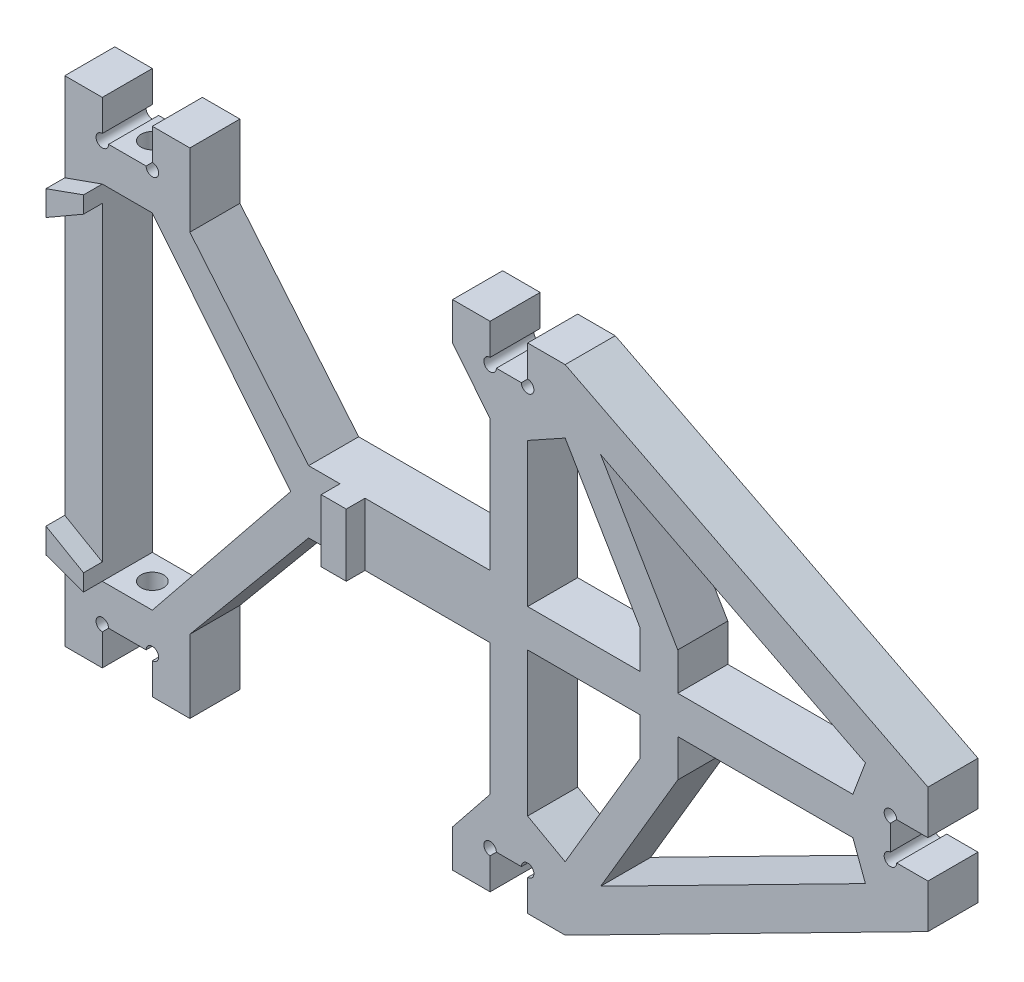
SolidWorks part; units mm, degrees
ref_plane "前视基准面" through (0, 0, 0) normal (0, 0, 1) x (1, 0, 0)
ref_plane "上视基准面" through (0, 0, 0) normal (0, 1, 0) x (1, 0, 0)
ref_plane "右视基准面" through (0, 0, 0) normal (1, 0, 0) x (0, 0, -1)
sketch "草图1" plane through (0, 0, 0) normal (0, 0, 1) x (1, 0, 0)
  line L12 (66, -1) -> (66, 1)
  line L13 (69, -5) -> (40, -19.75)
  line L14 (40, -19.75) -> (37, -19.75)
  line L15 (34.5, -16.75) -> (36.5, -16.75)
  line L16 (31, -16.75) -> (31, -19.75)
  line L17 (34, 13) -> (34, 2.5)
  line L18 (34, 13) -> (31, 16.75)
  line L19 (31, 19.75) -> (34, 19.75)
  line L20 (34, 19.75) -> (34, 17.25)
  line L21 (34.5, 16.75) -> (36.5, 16.75)
  line L22 (37, 13) -> (37, 1.5)
  line L23 (34, -19.75) -> (31, -19.75)
  line L24 (34, -13) -> (31, -16.75)
  line L25 (34, -19.75) -> (34, -17.25)
  line L26 (42.8383, -14.9406) -> (49, -4.5)
  line L27 (46, -1.5) -> (37, -1.5)
  line L28 (34, -2.5) -> (34, -13)
  line L29 (40, 14.6667) -> (46, 4.5)
  line L30 (46, 4.5) -> (46, 1.5)
  line L31 (63, 1.5) -> (64, 4.1774)
  line L32 (49, -1.5) -> (49, -4.5)
  line L33 (49, 4.5) -> (49, 1.5)
  line L34 (49, 1.5) -> (63, 1.5)
  line L35 (37, -17.25) -> (37, -19.75)
  line L36 (37, -1.5) -> (37, -13)
  line L37 (46, -1.5) -> (46, -4.5)
  line L38 (37, 19.75) -> (37, 17.25)
  line L39 (37, -13) -> (40, -14.6667)
  line L40 (46, -4.5) -> (40, -14.6667)
  line L41 (37, 13) -> (40, 14.6667)
  line L42 (37, 1.5) -> (46, 1.5)
  line L43 (42.8383, 14.9406) -> (64, 4.1774)
  line L44 (42.8383, -14.9406) -> (64, -4.1774)
  line L45 (49, 4.5) -> (42.8383, 14.9406)
  line L46 (66.5, 1.5) -> (69, 1.5)
  line L47 (69, 5) -> (69, 1.5)
  line L48 (63, -1.5) -> (49, -1.5)
  line L49 (37, 19.75) -> (40, 19.75)
  line L50 (40, 19.75) -> (69, 5)
  line L51 (31, 19.75) -> (31, 16.75)
  line L52 (69, -5) -> (69, -1.5)
  line L53 (66.5, -1.5) -> (69, -1.5)
  line L54 (63, -1.5) -> (64, -4.1774)
  line L55 (34, -2.5) -> (19.4926, -2.5)
  line L56 (34, 2.5) -> (19.4926, 2.5)
  line L57 (10, -13.9159) -> (19.4926, -2.5)
  line L58 (10, -19.75) -> (10, -13.9159)
  line L59 (10, -19.75) -> (7, -19.75)
  line L60 (7, -17.25) -> (7, -19.75)
  line L61 (3.5, -16.75) -> (6.5, -16.75)
  line L62 (3, -19.75) -> (3, -17.25)
  line L63 (3, -19.75) -> (0, -19.75)
  line L64 (3, -13.75) -> (7, -13.75)
  line L66 (18.0651, 0) -> (7, -13.75)
  line L67 (3, 13.75) -> (7, 13.75)
  line L68 (0, 19.75) -> (3, 19.75)
  line L69 (3, 19.75) -> (3, 17.25)
  line L70 (6.5, 16.75) -> (3.5, 16.75)
  line L71 (7, 19.75) -> (7, 17.25)
  line L72 (7, 19.75) -> (10, 19.75)
  line L73 (19.4926, 2.5) -> (10, 13.9159)
  line L74 (10, 19.75) -> (10, 13.9159)
  line L75 (7, 13.75) -> (18.0651, 0)
  line L78 (0, 19.75) -> (0, -19.75)
  line L81 (3, 13.75) -> (3, -13.75)
  arc A0 (66, -1) -> (66.5, -1.5) centre (66, -1.5) ccw
  arc A1 (37, -17.25) -> (36.5, -16.75) centre (37, -16.75) ccw
  arc A2 (34.5, -16.75) -> (34, -17.25) centre (34, -16.75) ccw
  arc A3 (34, 17.25) -> (34.5, 16.75) centre (34, 16.75) ccw
  arc A4 (36.5, 16.75) -> (37, 17.25) centre (37, 16.75) ccw
  arc A5 (66.5, 1.5) -> (66, 1) centre (66, 1.5) ccw
  arc A6 (7, -17.25) -> (6.5, -16.75) centre (7, -16.75) ccw
  arc A7 (3, 17.25) -> (3.5, 16.75) centre (3, 16.75) ccw
  arc A8 (6.5, 16.75) -> (7, 17.25) centre (7, 16.75) ccw
  arc A9 (3.5, -16.75) -> (3, -17.25) centre (3, -16.75) ccw
  point P0 (0, 0)
extrude "凸台-拉伸1" add sketch "草图1" along normal blind 4
sketch "草图2" plane through (0, -16.75, 0) normal (0, -1, 0) x (1, 0, 0)
  line L0 (3.5, 4) -> (6.5, 4) construction
  line L1 (3, 4) -> (3, 0) construction
  line L2 (7, 4) -> (7, 0) construction
  circle A0 centre (5, 2) radius 0.9
  dimension "D1" = 1.8
  dimension "D2" = 2
  dimension "D3" = 2
  dimension "D4" = 2
extrude "切除-拉伸1" cut sketch "草图2" against normal blind 52
sketch "草图3" plane through (0, 0, 4) normal (0, 0, 1) x (1, 0, 0)
  line L0 (3, 12.413) -> (3, 13.75)
  line L1 (3, 12.413) -> (0, 10.681)
  line L2 (0, 12.681) -> (0, 10.681)
  line L3 (0, 12.681) -> (3, 13.75)
  line L4 (24, -2.5) -> (24, 2.5)
  line L5 (24, -2.5) -> (22, -2.5)
  line L6 (22, 2.5) -> (22, -2.5)
  line L7 (22, 2.5) -> (24, 2.5)
  line L8 (3, -13.75) -> (3, -12.413)
  line L9 (3, -13.75) -> (0, -12.681)
  line L10 (0, -10.681) -> (0, -12.681)
  line L11 (0, -10.681) -> (3, -12.413)
extrude "凸台-拉伸2" add sketch "草图3" along normal blind 1.5
